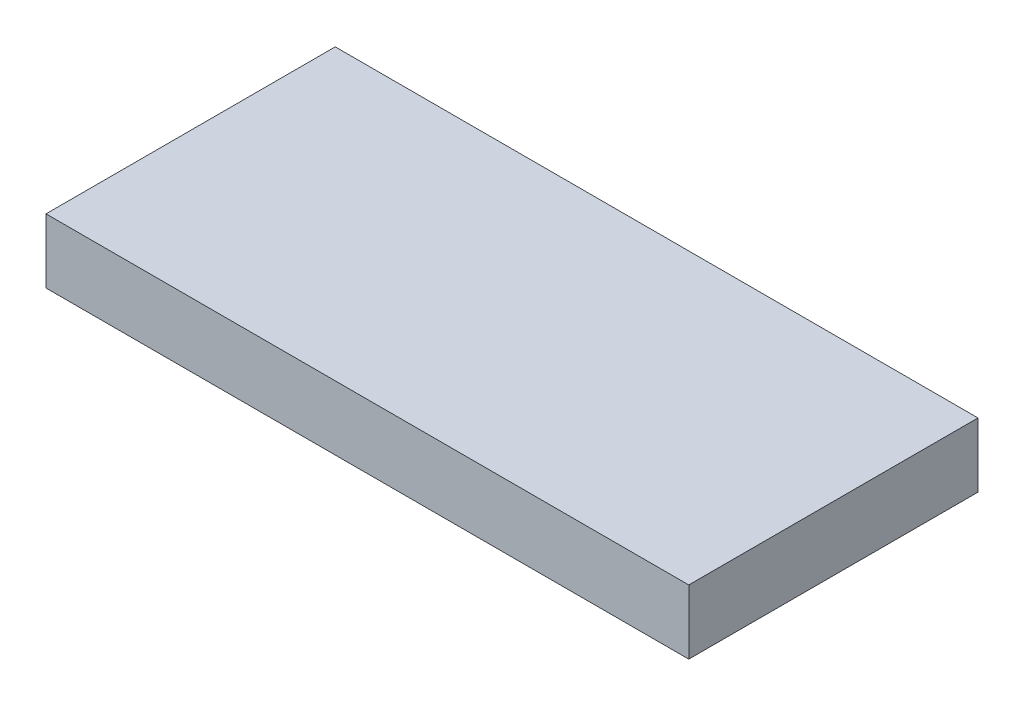
SolidWorks part; units mm, degrees
ref_plane "Front Plane" through (0, 0, 0) normal (0, 0, 1) x (1, 0, 0)
ref_plane "Top Plane" through (0, 0, 0) normal (0, 1, 0) x (1, 0, 0)
ref_plane "Right Plane" through (0, 0, 0) normal (1, 0, 0) x (0, 0, -1)
sketch "Sketch1" plane through (0, 0, 0) normal (0, 1, 0) x (1, 0, 0)
  line L1 (50, -22.5) -> (-50, -22.5)
  line L2 (50, -22.5) -> (50, 22.5)
  line L3 (50, 22.5) -> (-50, 22.5)
  line L4 (-50, -22.5) -> (-50, 22.5)
  line L5 (50, -22.5) -> (-50, 22.5) construction
  line L6 (50, 22.5) -> (-50, -22.5) construction
  point P0 (0, 0)
  dimension "D1" = 100
  dimension "D2" = 45
extrude "Boss-Extrude1" add sketch "Sketch1" along normal blind 10
